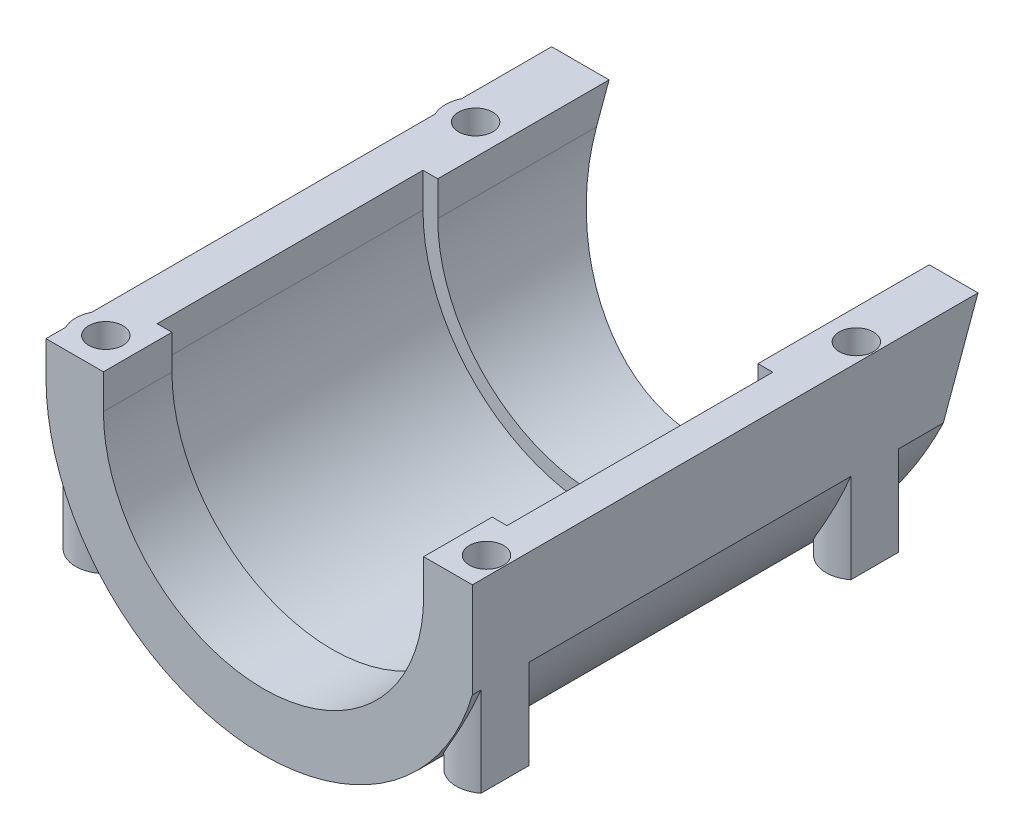
SolidWorks part; units mm, degrees
ref_plane "Front Plane" through (0, 0, 0) normal (0, 0, 1) x (1, 0, 0)
ref_plane "Top Plane" through (0, 0, 0) normal (0, 1, 0) x (1, 0, 0)
ref_plane "Right Plane" through (0, 0, 0) normal (1, 0, 0) x (0, 0, -1)
ref_axis "Axis1" through (0, 0, 55) along (0, 0, -1)
sketch "Sketch1" plane through (0, 0, 0) normal (0, 1, 0) x (1, 0, 0)
  line L0 (23.368, 44.4) -> (31.75, 44.4)
  line L1 (31.75, 44.4) -> (31.75, -29.4)
  line L2 (31.75, -29.4) -> (23.368, -29.4)
  line L3 (23.368, -29.4) -> (23.368, -19.4)
  line L4 (23.368, -19.4) -> (25.527, -19.4)
  line L5 (25.527, -19.4) -> (25.527, 19.4)
  line L6 (25.527, 19.4) -> (23.368, 19.4)
  line L7 (23.368, 19.4) -> (23.368, 44.4)
  line L8 (0, -54.785) -> (0, 54.785) construction
  point P10 (23.368, -32.7188)
  point P11 (25.527, 0)
  dimension "D1" = 25.527
  dimension "D2" = 31.75
  dimension "D3" = 23.368
  dimension "D4" = 25
  dimension "D5" = 38.8
  dimension "D6" = 10
revolve "Revolve1" add sketch "Sketch1" angle 180 about axis through (0, 0, 55) along (0, 0, -1)
sketch "Sketch3" plane through (0, 0, 0) normal (0, 1, 0) x (1, 0, 0)
  line L0 (23.368, 44.4) -> (23.368, 19.4) construction
  line L1 (23.368, 19.4) -> (25.527, 19.4) construction
  line L2 (25.527, 19.4) -> (25.527, -19.4) construction
  line L3 (25.527, -19.4) -> (23.368, -19.4) construction
  line L4 (23.368, -19.4) -> (23.368, -29.4) construction
  line L5 (23.368, -29.4) -> (31.75, -29.4) construction
  line L6 (31.75, -29.4) -> (31.75, 44.4) construction
  line L7 (31.75, 44.4) -> (23.368, 44.4) construction
  line L8 (-23.368, 19.4) -> (-23.368, 44.4) construction
  line L9 (-23.368, 44.4) -> (-31.75, 44.4) construction
  line L10 (-31.75, 44.4) -> (-31.75, -29.4) construction
  line L11 (-31.75, -29.4) -> (-23.368, -29.4) construction
  line L12 (-23.368, -29.4) -> (-23.368, -19.4) construction
  line L13 (-23.368, -19.4) -> (-25.527, -19.4) construction
  line L14 (-25.527, -19.4) -> (-25.527, 19.4) construction
  line L15 (-25.527, 19.4) -> (-23.368, 19.4) construction
  line L16 (23.368, 44.4) -> (23.368, 19.4)
  line L17 (23.368, 19.4) -> (25.527, 19.4)
  line L18 (25.527, 19.4) -> (25.527, -19.4)
  line L19 (25.527, -19.4) -> (23.368, -19.4)
  line L20 (23.368, -19.4) -> (23.368, -29.4)
  line L21 (23.368, -29.4) -> (31.75, -29.4)
  line L22 (31.75, -29.4) -> (31.75, 44.4)
  line L23 (31.75, 44.4) -> (23.368, 44.4)
  line L24 (-23.368, 19.4) -> (-23.368, 44.4)
  line L25 (-23.368, 44.4) -> (-31.75, 44.4)
  line L26 (-31.75, 44.4) -> (-31.75, -29.4)
  line L27 (-31.75, -29.4) -> (-23.368, -29.4)
  line L28 (-23.368, -29.4) -> (-23.368, -19.4)
  line L29 (-23.368, -19.4) -> (-25.527, -19.4)
  line L30 (-25.527, -19.4) -> (-25.527, 19.4)
  line L31 (-25.527, 19.4) -> (-23.368, 19.4)
extrude "Boss-Extrude1" add sketch "Sketch3" along normal blind 5.0289
sketch "Sketch4" plane through (0, 5.0289, 0) normal (0, 1, 0) x (1, 0, 0)
  line L0 (0, -20.2284) -> (0, 20.2284) construction
  line L1 (-27.7813, 29.3375) -> (27.7812, 29.3375) construction
  line L2 (-27.7813, 29.3375) -> (-27.7813, -24.6375) construction
  line L3 (-27.7813, -24.6375) -> (27.7812, -24.6375) construction
  line L4 (27.7812, 29.3375) -> (27.7812, -24.6375) construction
  line L5 (-27.7813, 29.3375) -> (27.7812, -24.6375) construction
  line L6 (-27.7813, -24.6375) -> (27.7812, 29.3375) construction
  line L7 (-23.368, -29.4) -> (23.368, -29.4) construction
  circle A0 centre (-27.7813, 29.3375) radius 2.5
  circle A1 centre (27.7812, 29.3375) radius 2.5
  circle A2 centre (27.7812, -24.6375) radius 2.5
  circle A3 centre (-27.7813, -24.6375) radius 2.5
  point P0 (0, 2.35)
  dimension "D4" = 5
  dimension "D1" = 53.975
  dimension "D2" = 55.5625
  dimension "D3" = 31.75
extrude "Cut-Extrude1" cut sketch "Sketch4" against normal through all
sketch "Sketch5" plane through (0, 5.0289, 0) normal (0, 1, 0) x (1, 0, 0)
  line L0 (-23.368, 19.4) -> (-23.368, 44.4) construction
  circle A0 centre (-27.7813, 29.3375) radius 4.4133
  circle A1 centre (-27.7813, -24.6375) radius 4.4133
  circle A2 centre (27.7812, -24.6375) radius 4.4133
  circle A3 centre (27.7812, 29.3375) radius 4.4133
  circle A4 centre (27.7812, -24.6375) radius 2.5
  circle A5 centre (27.7812, -24.6375) radius 2.5 construction
  circle A6 centre (-27.7813, -24.6375) radius 2.5
  circle A7 centre (-27.7813, 29.3375) radius 2.5
  circle A8 centre (27.7812, 29.3375) radius 2.5
  circle A9 centre (-27.7813, -24.6375) radius 2.5 construction
  circle A10 centre (-27.7813, 29.3375) radius 2.5 construction
  circle A11 centre (27.7812, 29.3375) radius 2.5 construction
extrude "Boss-Extrude2" add sketch "Sketch5" against normal blind 26.9875
sketch "Sketch6" plane through (0, 0, 0) normal (1, 0, 0) x (0, 0, -1)
  line L0 (44.4, 5.0289) -> (31.0136, -31.75)
  line L1 (-29.4, -31.75) -> (44.4, -31.75) construction
  line L2 (31.0136, -31.75) -> (44.4, -31.75)
  line L3 (44.4, -31.75) -> (44.4, 5.0289)
  dimension "D1" = 20
extrude "Cut-Extrude2" cut sketch "Sketch6" against normal through all both and the other way through all
sketch "Sketch8" plane through (0, 5.0289, 0) normal (0, 1, 0) x (1, 0, 0)
  line L0 (31.75, 44.4) -> (23.368, 44.4) construction
  line L1 (30.48, 44.4) -> (38.3892, 44.4)
  line L2 (30.48, 44.4) -> (30.48, -29.4)
  line L3 (30.48, -29.4) -> (38.3892, -29.4)
  line L4 (38.3892, 44.4) -> (38.3892, -29.4)
  line L5 (30.48, 44.4) -> (38.3892, -29.4) construction
  line L6 (30.48, -29.4) -> (38.3892, 44.4) construction
  line L7 (23.368, -29.4) -> (31.75, -29.4) construction
  line L8 (31.75, 31.2677) -> (31.75, 44.4) construction
  point P4 (34.4346, 7.5)
  dimension "D1" = 1.27
extrude "Cut-Extrude7" cut sketch "Sketch8" against normal through all both and the other way through all
